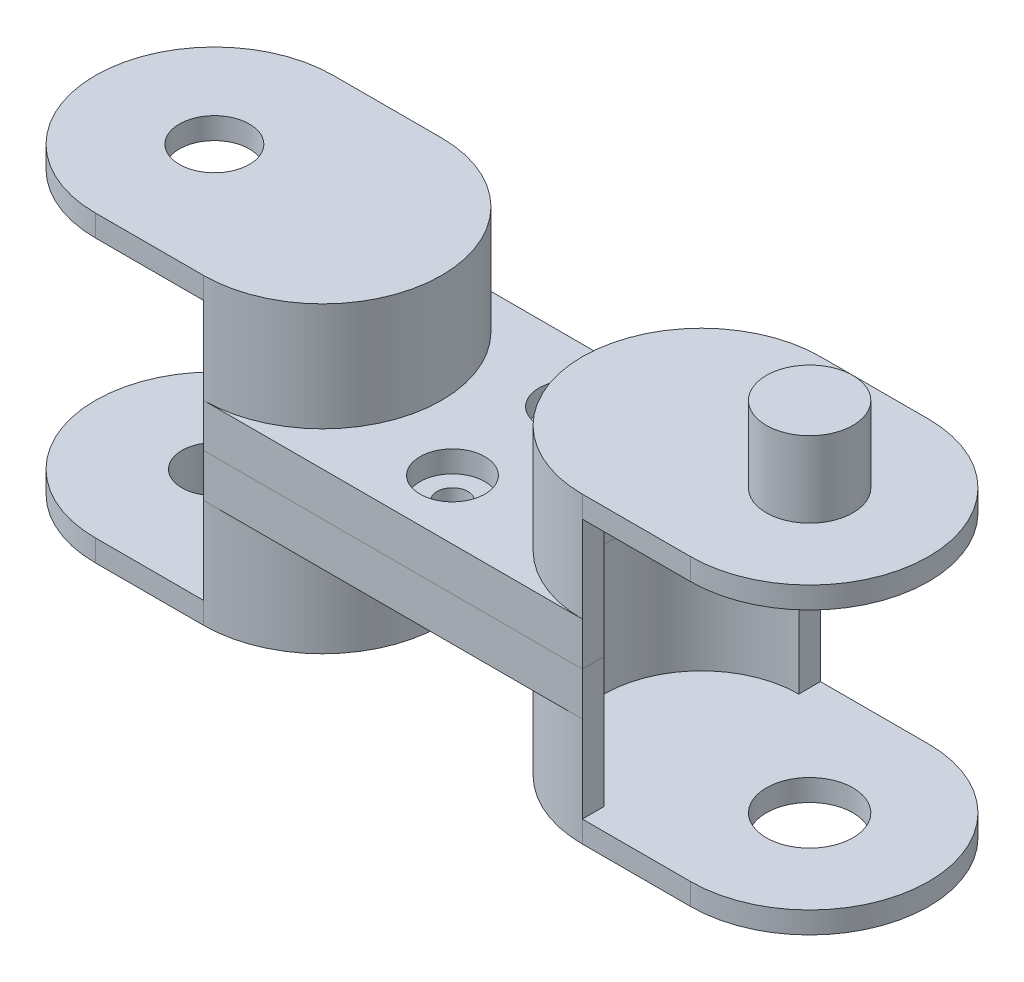
SolidWorks part; units mm, degrees
ref_plane "Front Plane" through (0, 0, 0) normal (0, 0, 1) x (1, 0, 0)
ref_plane "Top Plane" through (0, 0, 0) normal (0, 1, 0) x (1, 0, 0)
ref_plane "Right Plane" through (0, 0, 0) normal (1, 0, 0) x (0, 0, -1)
sketch "Sketch1" plane through (0, 0, 0) normal (0, 1, 0) x (1, 0, 0)
  line L0 (0, 0) -> (55, 0) construction
  line L1 (0, 11) -> (55, 11)
  line L2 (0, -11) -> (55, -11)
  arc A0 (0, 11) -> (0, -11) centre (0, 0) ccw
  arc A1 (55, -11) -> (55, 11) centre (55, 0) ccw
  circle A2 centre (0, 0) radius 3.2353
  circle A3 centre (55, 0) radius 3
  point P3 (27.5, 0)
  dimension "D2" = 11
  dimension "D3" = 6
  dimension "D1" = 55
extrude "Boss-Extrude1" add sketch "Sketch1" along normal blind 2
sketch "Sketch2" plane through (0, 0, 0) normal (0, -1, 0) x (1, 0, 0)
  line L0 (0, 0) -> (10, 0) construction
  line L3 (55, 0) -> (45, 0) construction
  line L6 (10, 11) -> (45, 11)
  line L7 (10, -11) -> (45, -11)
  arc A1 (10, -11) -> (10, 11) centre (10, 0) ccw
  arc A3 (45, 11) -> (45, -11) centre (45, 0) ccw
  point P3 (5, 0)
  point P8 (50, 0)
  dimension "D1" = 10
  dimension "D2" = 10
extrude "Cut-Extrude1" cut sketch "Sketch2" against normal blind 2
sketch "Sketch3" plane through (0, 0, 0) normal (0, -1, 0) x (1, 0, 0)
  line L0 (45, 11) -> (45, 9)
  line L1 (10, 11) -> (10, 9)
  line L2 (10, -9) -> (10, -11)
  line L3 (45, -9) -> (45, -11)
  arc A0 (45, 11) -> (45, -11) centre (45, 0) ccw
  arc A1 (10, -11) -> (10, 11) centre (10, 0) ccw
  arc A2 (10, -9) -> (10, 9) centre (10, 0) ccw
  arc A3 (45, 9) -> (45, -9) centre (45, 0) ccw
  dimension "D1" = 2
  dimension "D2" = 2
extrude "Boss-Extrude2" add sketch "Sketch3" along normal blind 12
sketch "Sketch4" plane through (0, -12, 0) normal (0, -1, 0) x (1, 0, 0)
  line L8 (10, -9) -> (10, -11)
  line L13 (10, 11) -> (45, 11)
  line L14 (10, 11) -> (10, 9)
  line L15 (10, -11) -> (45, -11)
  line L16 (45, 11) -> (45, 9)
  line L17 (45, -9) -> (45, -11)
  arc A10 (45, 9) -> (45, -9) centre (45, 0) ccw
  arc A11 (10, -9) -> (10, 9) centre (10, 0) ccw
  point P8 (27.5, 0)
extrude "Boss-Extrude3" add sketch "Sketch4" against normal blind 4
ref_plane "Plane1" through (0, -12, 0) normal (0, -1, 0) x (-1, 0, 0)
mirror "Mirror2" about plane through (0, -12, 0) normal (0, -1, 0) of bodies 106
sketch "Sketch5" plane through (0, 2, 0) normal (0, 1, 0) x (1, 0, 0)
  circle A0 centre (55, 0) radius 3
  circle A1 centre (55, 0) radius 4
  dimension "D1" = 6
  dimension "D2" = 1
extrude "Boss-Extrude4" add sketch "Sketch5" along normal blind 5
sketch "Sketch6" plane through (0, 7, 0) normal (0, 1, 0) x (1, 0, 0)
  circle A0 centre (55, 0) radius 4
extrude "Boss-Extrude5" add sketch "Sketch6" along normal blind 2
sketch "Sketch7" plane through (0, -26, 0) normal (0, -1, 0) x (1, 0, 0)
  circle A0 centre (0, 0) radius 3
  circle A2 centre (0, 0) radius 3.754
  dimension "D1" = 6
extrude "Boss-Extrude6" add sketch "Sketch7" against normal blind 2
sketch "Sketch9" plane through (0, -26, 0) normal (0, -1, 0) x (1, 0, 0)
  circle A0 centre (0, 0) radius 3
  circle A1 centre (0, 0) radius 4
  dimension "D1" = 1
extrude "Boss-Extrude7" add sketch "Sketch9" along normal blind 5
sketch "Sketch10" plane through (0, -31, 0) normal (0, -1, 0) x (1, 0, 0)
  circle A0 centre (0, 0) radius 4
  dimension "D1" = 8
extrude "Boss-Extrude8" add sketch "Sketch10" along normal blind 2
sketch "Sketch12" plane through (0, 2, 0) normal (0, 1, 0) x (1, 0, 0)
  circle A0 centre (0, 0) radius 3
  circle A1 centre (0, 0) radius 3.9363
extrude "Boss-Extrude9" add sketch "Sketch12" against normal blind 2
sketch "Sketch14" plane through (0, 2, 0) normal (0, 1, 0) x (1, 0, 0)
  circle A0 centre (0, 0) radius 4
  dimension "D1" = 8
extrude "Cut-Extrude3" cut sketch "Sketch14" against normal blind 5
sketch "Sketch15" plane through (0, -26, 0) normal (0, -1, 0) x (1, 0, 0)
  circle A0 centre (55, 0) radius 4
  dimension "D1" = 8
extrude "Cut-Extrude4" cut sketch "Sketch15" against normal blind 5
sketch "Sketch16" plane through (0, -8, 0) normal (0, 1, 0) x (1, 0, 0)
  line L0 (27.5, 11) -> (27.5, 0) construction
  line L1 (10, 11) -> (45, 11) construction
  line L3 (23.7408, 0) -> (31.2592, 0) construction
  line L4 (27.5, 0) -> (27.5, -11) construction
  line L5 (45, -11) -> (10, -11) construction
  circle A0 centre (27.5, 5.5) radius 1.5
  circle A1 centre (27.5, -5.5) radius 1.5
  point P9 (27.5, 0)
  dimension "D1" = 3
extrude "Cut-Extrude5" cut sketch "Sketch16" against normal through all draft 2
sketch "Sketch17" plane through (0, -8, 0) normal (0, 1, 0) x (1, 0, 0)
  line L0 (21.4919, 0) -> (33.4133, 0) construction
  circle A0 centre (27.5, 5.5) radius 3
  circle A1 centre (27.5, -5.5) radius 3
  dimension "D1" = 6
extrude "Cut-Extrude6" cut sketch "Sketch17" against normal blind 2
